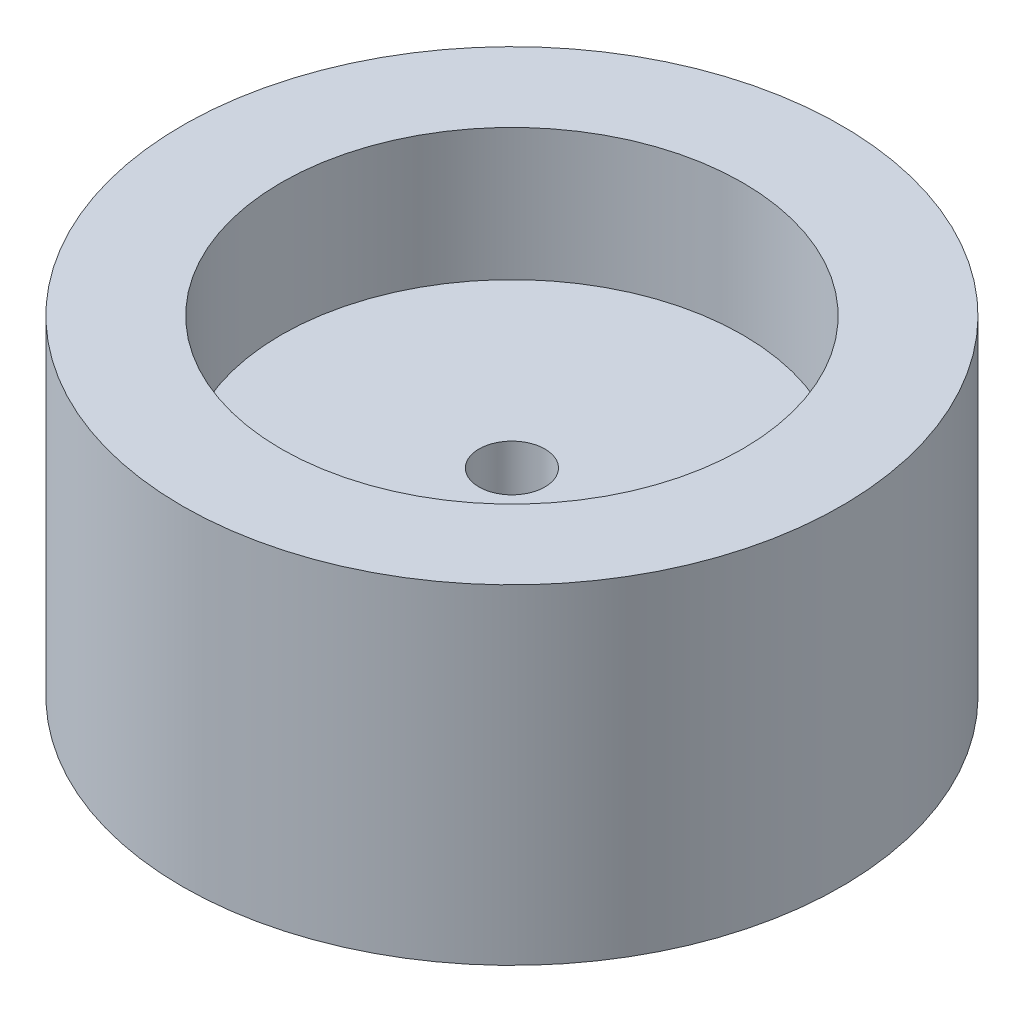
SolidWorks part; units mm, degrees
ref_plane "前视基准面" through (0, 0, 0) normal (0, 0, 1) x (1, 0, 0)
ref_plane "上视基准面" through (0, 0, 0) normal (0, 1, 0) x (1, 0, 0)
ref_plane "右视基准面" through (0, 0, 0) normal (1, 0, 0) x (0, 0, -1)
other "Configuration Table"
sketch "草图1" plane through (0, 0, 0) normal (0, 1, 0) x (1, 0, 0)
  circle A0 centre (0, 0) radius 25
  dimension "D1" = 50
extrude "凸台-拉伸1" add sketch "草图1" along normal blind 25
sketch "草图2" plane through (0, 0, 0) normal (0, -1, 0) x (1, 0, 0)
  circle A0 centre (0, 0) radius 17.5
  dimension "D1" = 35
extrude "切除-拉伸1" cut sketch "草图2" against normal blind 10
ref_plane "基准面1" through (0, 12.5, 0) normal (0, -1, 0) x (-1, 0, 0)
mirror "镜向1" about plane through (0, 12.5, 0) normal (0, -1, 0) of "切除-拉伸1"
sketch "草图3" plane through (0, 10, 0) normal (0, -1, 0) x (1, 0, 0)
  circle A0 centre (0, 0) radius 2.5
  dimension "D1" = 5
extrude "切除-拉伸2" cut sketch "草图3" against normal through all
